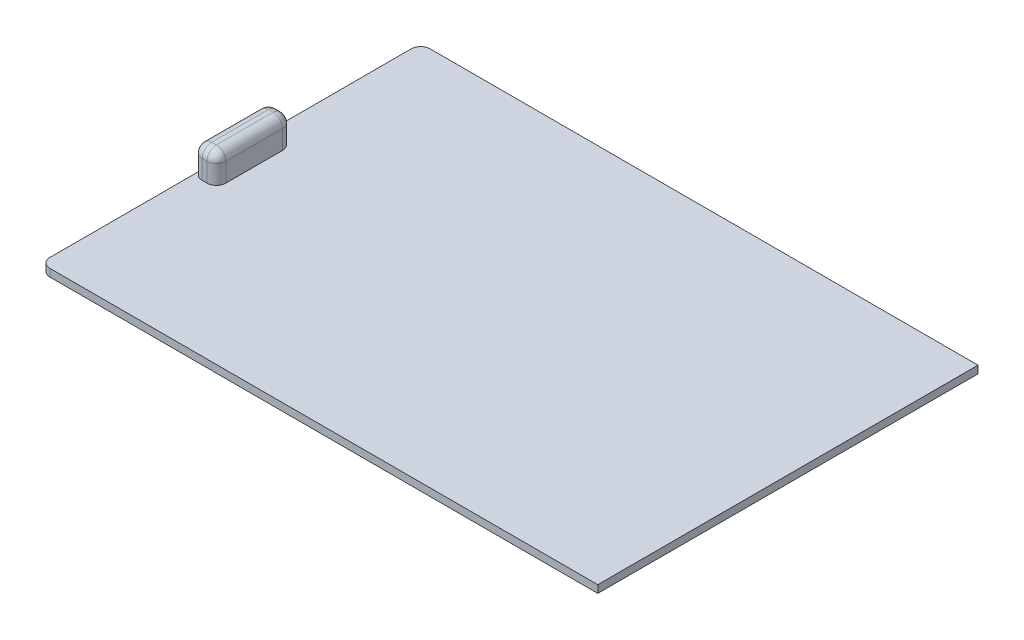
SolidWorks part; units mm, degrees
ref_plane "Front Plane" through (0, 0, 0) normal (0, 0, 1) x (1, 0, 0)
ref_plane "Top Plane" through (0, 0, 0) normal (0, 1, 0) x (1, 0, 0)
ref_plane "Right Plane" through (0, 0, 0) normal (1, 0, 0) x (0, 0, -1)
sketch "Sketch1" plane through (0, 0, 0) normal (0, 1, 0) x (1, 0, 0)
  line L1 (0, -80.5) -> (118, -80.5)
  line L2 (0, -80.5) -> (0, 0)
  line L3 (0, 0) -> (118, 0)
  line L4 (118, -80.5) -> (118, 0)
  dimension "D1" = 118
  dimension "D2" = 80.5
extrude "lid extrude" add sketch "Sketch1" along normal blind 1.6
fillet "lid edge fillet" radius 2 2 edges at (0, 0.8, 0) (0, 0.8, 80.5)
sketch "Sketch2" plane through (0, 1.6, 0) normal (0, 1, 0) x (1, 0, 0)
  line L1 (0, -32.25) -> (5, -32.25)
  line L2 (5, -32.25) -> (5, -48.25)
  line L3 (5, -48.25) -> (0, -48.25)
  line L4 (0, -2) -> (0, -78.5) construction
  line L5 (0, -32.25) -> (0, -48.25)
  dimension "D1" = 5
  dimension "D2" = 16
  dimension "D3" = 30.25
extrude "Boss-Extrude2" add sketch "Sketch2" along normal blind 6 contours L1 L2 L3 L5
fillet "Fillet2" radius 2 8 edges at (5, 4.6, 32.25) (5, 4.6, 48.25) (0, 4.6, 48.25) (0, 4.6, 32.25) (2.5, 7.6, 32.25) (2.5, 7.6, 48.25) (5, 7.6, 40.25) (0, 7.6, 40.25)
